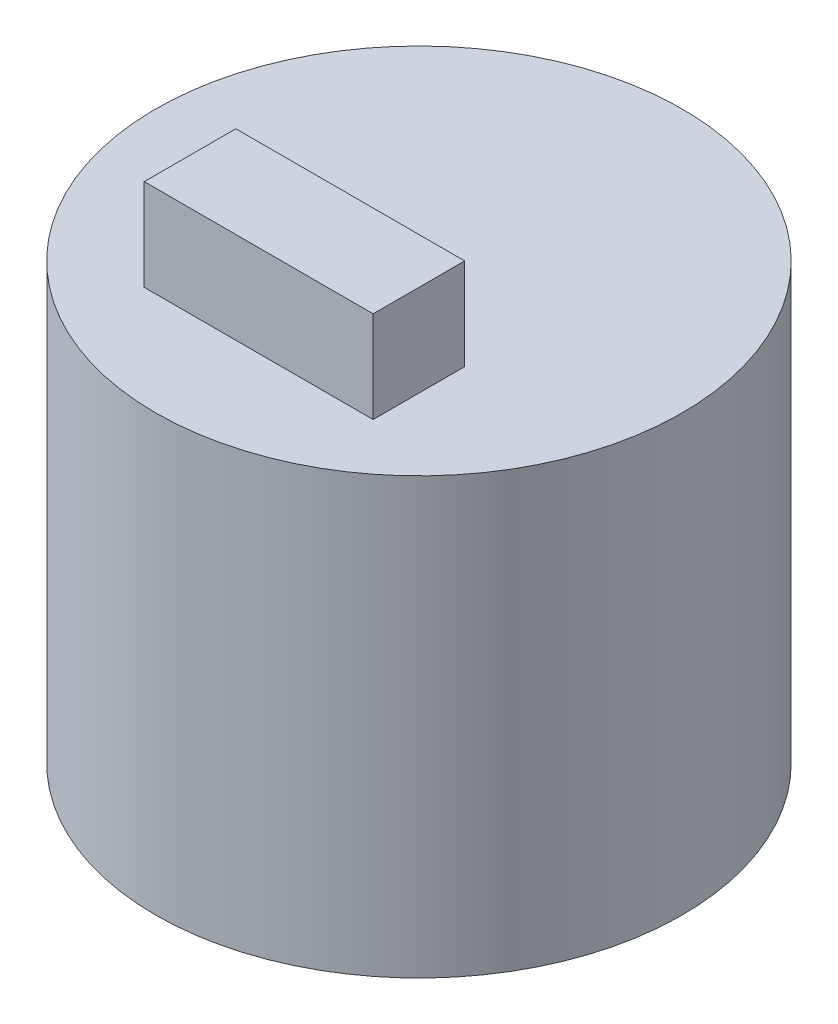
SolidWorks part; units mm, degrees
material "PMMA"
ref_plane "Front Plane" through (0, 0, 0) normal (0, 0, 1) x (1, 0, 0)
ref_plane "Top Plane" through (0, 0, 0) normal (0, 1, 0) x (1, 0, 0)
ref_plane "Right Plane" through (0, 0, 0) normal (1, 0, 0) x (0, 0, -1)
sketch "Sketch1" plane through (0, 0, 0) normal (0, 1, 0) x (1, 0, 0)
  circle A0 centre (0, 0) radius 11.5
  dimension "D1" = 23
extrude "Boss-Extrude1" add sketch "Sketch1" along normal blind 19
sketch "Sketch2" plane through (0, 19, 0) normal (0, 1, 0) x (1, 0, 0)
  line L0 (-5, -3) -> (5, -3)
  line L1 (-5, -3) -> (-5, -7)
  line L2 (5, -3) -> (5, -7)
  line L3 (-5, -7) -> (5, -7)
  line L4 (-5, -3) -> (5, -7) construction
  line L5 (5, -3) -> (-5, -7) construction
  line L6 (0, 0) -> (0, -5) construction
  point P1 (0, -5)
  dimension "D1" = 10
  dimension "D2" = 4
  dimension "D3" = 5
extrude "Boss-Extrude2" add sketch "Sketch2" along normal blind 4
sketch "Sketch3" plane through (0, 0, 0) normal (0, -1, 0) x (1, 0, 0)
  line L0 (0, 8.5) -> (0, -8.5) construction
  circle A0 centre (0, 0) radius 3.5
  circle A1 centre (0, 8.5) radius 1.25
  circle A2 centre (0, -8.5) radius 1.25
  dimension "D1" = 7
  dimension "D2" = 17
  dimension "D3" = 2.5
extrude "Cut-Extrude1" cut sketch "Sketch3" against normal blind 9
